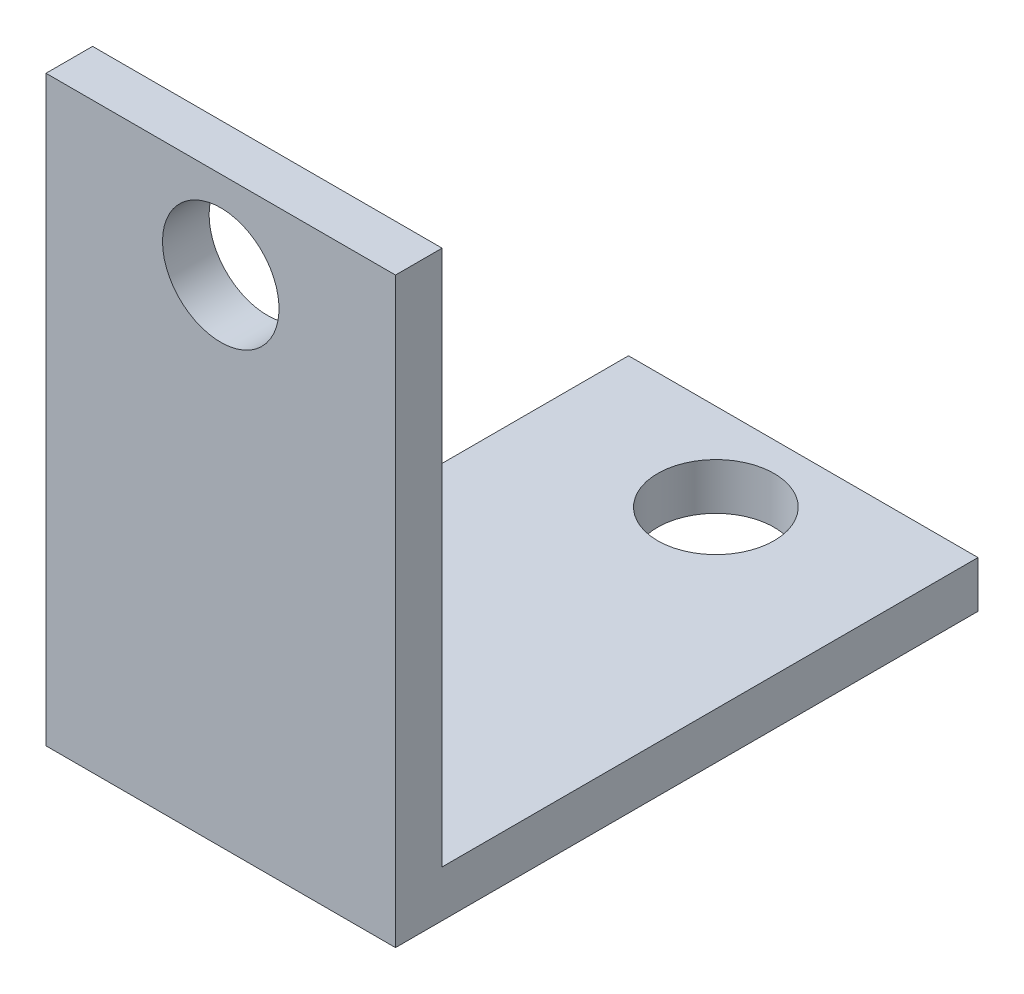
SolidWorks part; units mm, degrees
material "Yumuşak Demir"
ref_plane "Ön Düzlem" through (0, 0, 0) normal (0, 0, 1) x (1, 0, 0)
ref_plane "Üst Düzlem" through (0, 0, 0) normal (0, 1, 0) x (1, 0, 0)
ref_plane "Sağ Düzlem" through (0, 0, 0) normal (1, 0, 0) x (0, 0, -1)
sketch "Çizim1" plane through (0, 0, 0) normal (0, 1, 0) x (1, 0, 0)
  line L1 (-7.5, -12.5) -> (7.5, -12.5)
  line L2 (-7.5, -12.5) -> (-7.5, 12.5)
  line L3 (-7.5, 12.5) -> (7.5, 12.5)
  line L4 (7.5, -12.5) -> (7.5, 12.5)
  circle A0 centre (0, 8.75) radius 2.5
  dimension "D3" = 5
  dimension "D6" = 3.75
  dimension "D1" = 25
  dimension "D2" = 15
  dimension "D4" = 7.5
  dimension "D5" = 12.5
extrude "Yükseklik-Ekstrüzyon1" add sketch "Çizim1" along normal blind 2
sketch "Çizim2" plane through (0, 2, 0) normal (0, 1, 0) x (1, 0, 0)
  line L0 (7.5, -12.5) -> (7.5, 12.5) construction
  line L1 (-7.5, -12.5) -> (7.5, -12.5)
  line L2 (-7.5, -12.5) -> (-7.5, -10.5)
  line L3 (-7.5, -10.5) -> (7.5, -10.5)
  line L4 (7.5, -12.5) -> (7.5, -10.5)
  dimension "D1" = 2
extrude "Yükseklik-Ekstrüzyon2" add sketch "Çizim2" along normal blind 23
sketch "Çizim3" plane through (0, 0, 10.5) normal (0, 0, -1) x (-1, 0, 0)
  line L0 (-7.5, 25) -> (7.5, 25) construction
  line L1 (-7.5, 25) -> (-7.5, 2) construction
  circle A0 centre (0, 21.25) radius 2.5
  dimension "D1" = 5
  dimension "D2" = 3.75
  dimension "D3" = 7.5
extrude "Kes-Ekstrüzyon1" cut sketch "Çizim3" against normal blind 13
